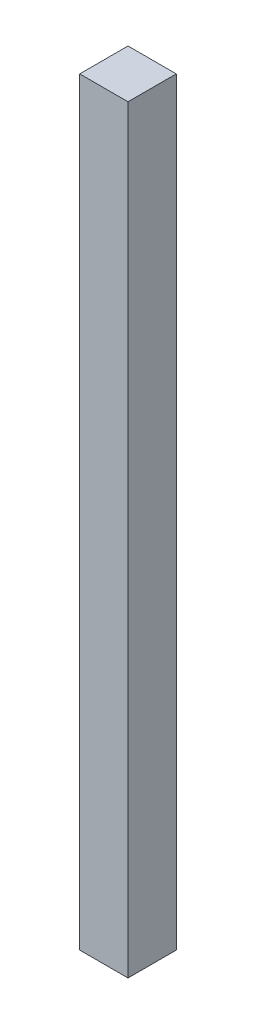
SolidWorks part; units mm, degrees
ref_plane "Front Plane" through (0, 0, 0) normal (0, 0, 1) x (1, 0, 0)
ref_plane "Top Plane" through (0, 0, 0) normal (0, 1, 0) x (1, 0, 0)
ref_plane "Right Plane" through (0, 0, 0) normal (1, 0, 0) x (0, 0, -1)
sketch "Sketch1" plane through (0, 0, 0) normal (0, 1, 0) x (1, 0, 0)
  line L1 (0, 0) -> (25.4, 0)
  line L2 (0, 0) -> (0, 25.4)
  line L3 (0, 25.4) -> (25.4, 25.4)
  line L4 (25.4, 0) -> (25.4, 25.4)
  dimension "D1" = 25.4
extrude "Boss-Extrude1" add sketch "Sketch1" along normal blind 399.2
